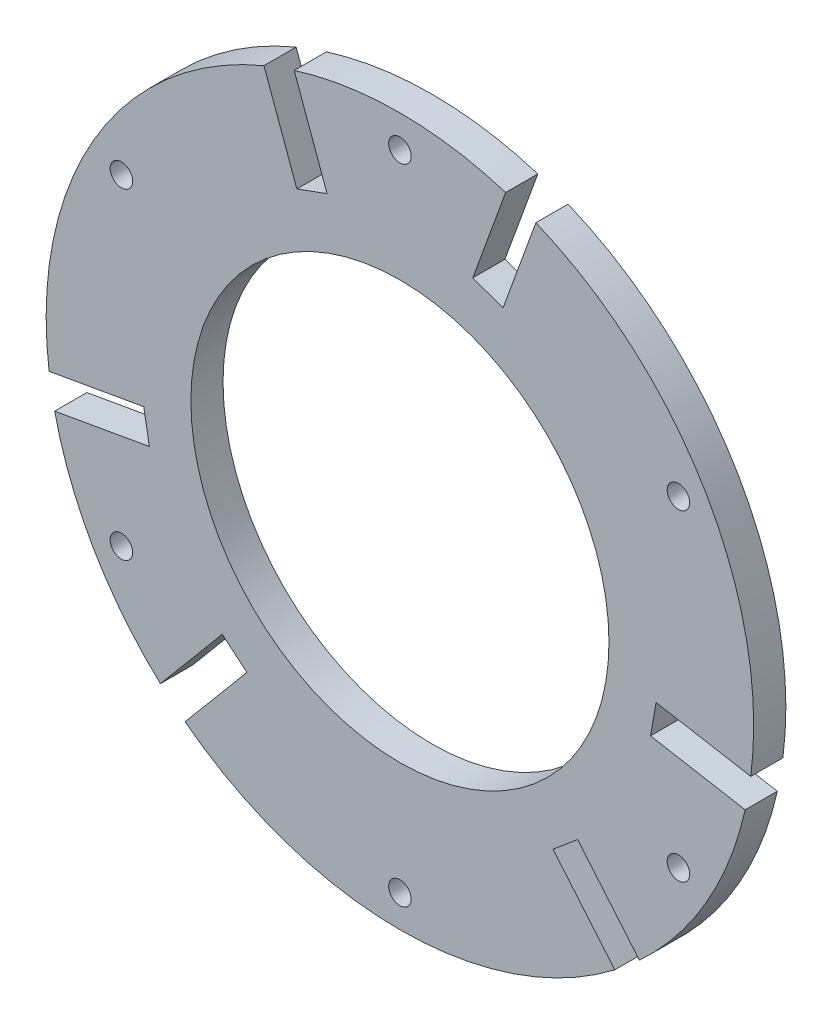
SolidWorks part; units mm, degrees
ref_plane "Alzado" through (0, 0, 0) normal (0, 0, 1) x (1, 0, 0)
ref_plane "Planta" through (0, 0, 0) normal (0, 1, 0) x (1, 0, 0)
ref_plane "Vista lateral" through (0, 0, 0) normal (1, 0, 0) x (0, 0, -1)
sketch "Croquis1" plane through (0, 0, 0) normal (0, 0, 1) x (1, 0, 0)
  circle A0 centre (0, 0) radius 55
  dimension "D1" = 110
extrude "Saliente-Extruir1" add sketch "Croquis1" along normal blind 5
sketch "Croquis2" plane through (0, 0, 5) normal (0, 0, 1) x (1, 0, 0)
  line L0 (0, 59.1895) -> (0, 0) construction
  line L1 (51.2612, -29.5938) -> (0.0016, 0.0009) construction
  line L2 (-51.258, -29.5957) -> (0.0016, -0.0009) construction
  line L3 (0.0016, 0.0009) -> (-22.0364, 60.5499) construction
  line L4 (-0.0016, 0.0009) -> (22.0364, 60.5499) construction
  line L5 (-21.1586, 50.8287) -> (-16.0283, 36.7333)
  line L6 (-16.0283, 36.7333) -> (-11.3299, 38.4434)
  line L7 (-11.3299, 38.4434) -> (-16.4602, 52.5388)
  line L8 (-16.4602, 52.5388) -> (-21.1586, 50.8287)
  line L9 (0, -0.0018) -> (63.456, -11.1908) construction
  line L10 (0.0016, 0.0009) -> (41.4195, -49.359) construction
  line L11 (-0.0016, 0.0009) -> (-41.4195, -49.359) construction
  line L12 (0, -0.0018) -> (-63.456, -11.1908) construction
  line L13 (16.0283, 36.7333) -> (11.3299, 38.4434)
  line L14 (11.3299, 38.4434) -> (16.4602, 52.5388)
  line L15 (16.4602, 52.5388) -> (21.1586, 50.8287)
  line L16 (21.1586, 50.8287) -> (16.0283, 36.7333)
  line L17 (54.5982, -7.0904) -> (39.8261, -4.4857)
  line L18 (53.73, -12.0145) -> (54.5982, -7.0904)
  line L19 (38.9579, -9.4097) -> (53.73, -12.0145)
  line L20 (39.8261, -4.4857) -> (38.9579, -9.4097)
  line L21 (27.628, -29.0336) -> (37.2698, -40.5243)
  line L22 (37.2698, -40.5243) -> (33.4396, -43.7382)
  line L23 (33.4396, -43.7382) -> (23.7978, -32.2476)
  line L24 (23.7978, -32.2476) -> (27.628, -29.0336)
  line L25 (-33.4396, -43.7382) -> (-23.7978, -32.2476)
  line L26 (-37.2698, -40.5243) -> (-33.4396, -43.7382)
  line L27 (-27.628, -29.0336) -> (-37.2698, -40.5243)
  line L28 (-23.7978, -32.2476) -> (-27.628, -29.0336)
  line L29 (-38.9579, -9.4097) -> (-53.73, -12.0145)
  line L30 (-53.73, -12.0145) -> (-54.5982, -7.0904)
  line L31 (-54.5982, -7.0904) -> (-39.8261, -4.4857)
  line L32 (-39.8261, -4.4857) -> (-38.9579, -9.4097)
  circle A0 centre (0, 0) radius 10.063 construction
  circle A1 centre (0, 0) radius 55 construction
  circle A2 centre (0, 50) radius 1.75
  circle A3 centre (43.3013, 25) radius 1.75
  circle A4 centre (43.3013, -25) radius 1.75
  circle A5 centre (0, -50) radius 1.75
  circle A6 centre (-43.3013, -25) radius 1.75
  circle A7 centre (-43.3013, 25) radius 1.75
  circle A8 centre (0.0016, 0.0009) radius 32.5
  point P11 (0.0011, 0)
  point P15 (-16.2442, 44.636)
  point P23 (0, 0)
  point P31 (0, 0)
  point P53 (0, 0)
  point P64 (0, 0)
  dimension "D12" = 3.5
  dimension "D15" = 65
  dimension "D2" = 20
  dimension "D6" = 5
  dimension "D7" = 2.5
  dimension "D8" = 15
  dimension "D9" = 7.5
  dimension "D10" = 40
  dimension "D13" = 50
  dimension "D4" = 3
  dimension "D11" = 3
  dimension "D14" = 6
extrude "Cortar-Extruir1" cut sketch "Croquis2" against normal through all
